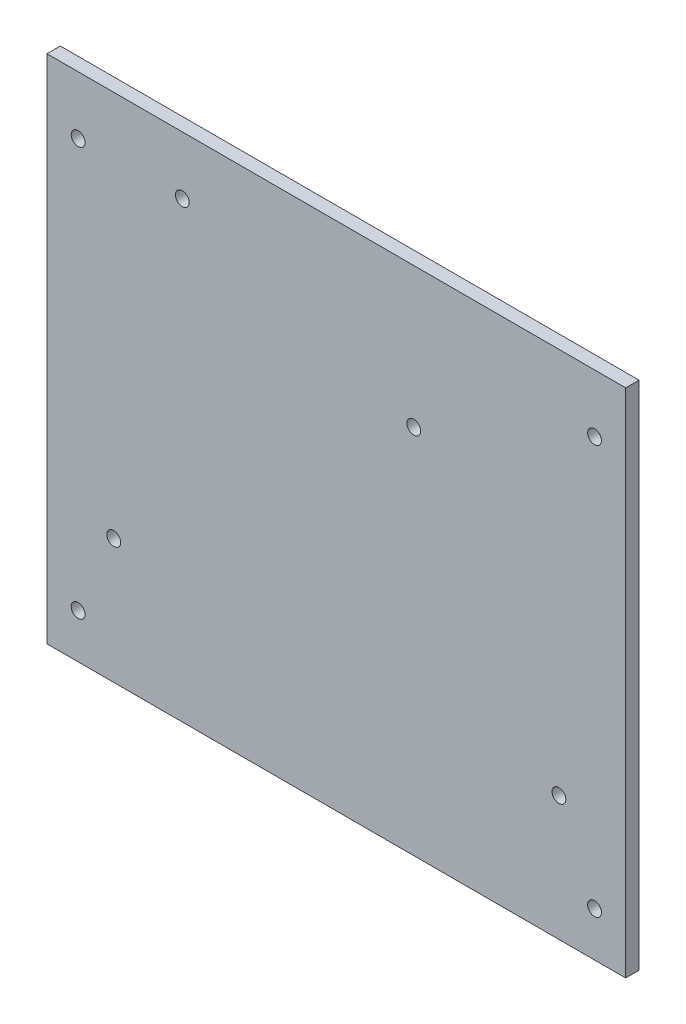
SolidWorks part; units mm, degrees
ref_plane "Alzado" through (0, 0, 0) normal (0, 0, 1) x (1, 0, 0)
ref_plane "Planta" through (0, 0, 0) normal (0, 1, 0) x (1, 0, 0)
ref_plane "Vista lateral" through (0, 0, 0) normal (1, 0, 0) x (0, 0, -1)
sketch "Croquis1" plane through (0, 0, 0) normal (0, 0, 1) x (1, 0, 0)
  line L1 (-65, -57.4) -> (65, -57.4)
  line L2 (-65, -57.4) -> (-65, 57.4)
  line L3 (-65, 57.4) -> (65, 57.4)
  line L4 (65, -57.4) -> (65, 57.4)
  line L5 (-65, -57.4) -> (65, 57.4) construction
  line L6 (-65, 57.4) -> (65, -57.4) construction
  point P0 (0, 0)
  dimension "D1" = 130
  dimension "D2" = 114.8
extrude "Saliente-Extruir1" add sketch "Croquis1" along normal blind 3
sketch "Croquis2" plane through (0, 0, 3) normal (0, 0, 1) x (1, 0, 0)
  line L0 (-65, 57.4) -> (-65, -57.4) construction
  line L1 (65, -57.4) -> (65, 57.4) construction
  line L2 (-65, -57.4) -> (65, -57.4) construction
  line L3 (65, 57.4) -> (-65, 57.4) construction
  circle A0 centre (-58, -47.4) radius 1.55
  circle A1 centre (-58, 44.4) radius 1.55
  circle A2 centre (58, 44.4) radius 1.55
  circle A3 centre (58, -47.4) radius 1.55
  circle A4 centre (-50, -29.4) radius 1.55
  circle A5 centre (50, -29.4) radius 1.55
  circle A6 centre (-34.6, 44.4) radius 1.55
  circle A7 centre (17.4, 25.96) radius 1.55
  dimension "D1" = 7
  dimension "D2" = 7
  dimension "D3" = 7
  dimension "D4" = 7
  dimension "D5" = 3.1
  dimension "D6" = 10
  dimension "D7" = 10
  dimension "D8" = 13
  dimension "D9" = 13
  dimension "D10" = 3.1
  dimension "D11" = 15
  dimension "D12" = 15
  dimension "D13" = 28
  dimension "D14" = 28
  dimension "D15" = 3.1
  dimension "D16" = 30.4
  dimension "D17" = 13
  dimension "D18" = 31.44
  dimension "D19" = 47.6
extrude "Cortar-Extruir1" cut sketch "Croquis2" against normal through all
